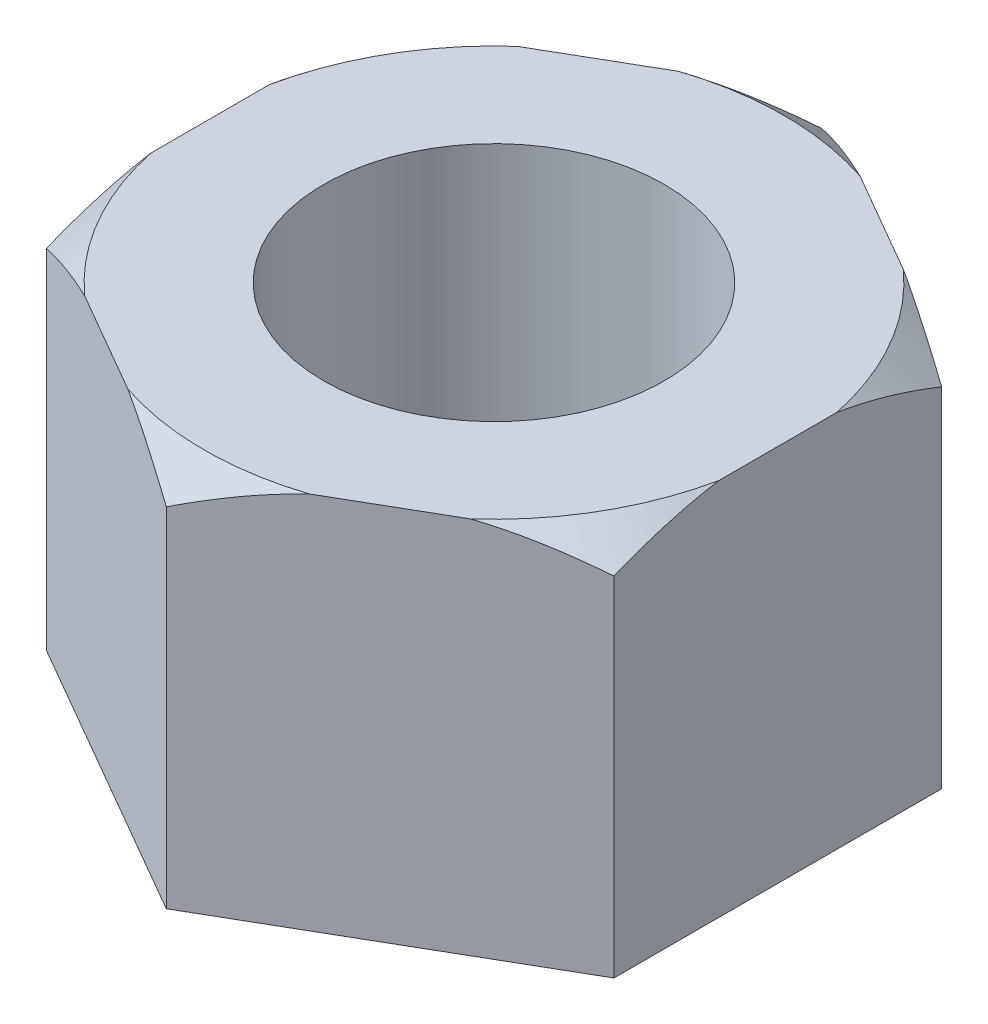
SolidWorks part; units mm, degrees
ref_plane "Front Plane" through (0, 0, 0) normal (0, 0, 1) x (1, 0, 0)
ref_plane "Top Plane" through (0, 0, 0) normal (0, 1, 0) x (1, 0, 0)
ref_plane "Right Plane" through (0, 0, 0) normal (1, 0, 0) x (0, 0, -1)
sketch "Sketch1" plane through (0, 0, 0) normal (0, 1, 0) x (1, 0, 0)
  line L1 (7.5, 4.3301) -> (0, 8.6603)
  line L2 (0, 8.6603) -> (-7.5, 4.3301)
  line L3 (-7.5, 4.3301) -> (-7.5, -4.3301)
  line L4 (-7.5, -4.3301) -> (0, -8.6603)
  line L5 (0, -8.6603) -> (7.5, -4.3301)
  line L6 (7.5, -4.3301) -> (7.5, 4.3301)
  circle A0 centre (0, 0) radius 7.5 construction
  dimension "D1" = 15
extrude "Boss-Extrude1" add sketch "Sketch1" along normal blind 10
sketch "Sketch2" plane through (0, 10, 0) normal (0, 1, 0) x (1, 0, 0)
  circle A0 centre (0, 0) radius 4.5
  dimension "D1" = 4.5
sketch "Sketch3" plane through (0, 0, 0) normal (1, 0, 0) x (0, 0, -1)
  line L0 (0, 0) -> (0, 10.0426) construction
  line L1 (-8.6603, 10) -> (-7.6603, 10)
  line L2 (-7.6603, 10) -> (-8.6603, 9.2)
  line L3 (-8.6603, 9.2) -> (-8.6603, 10)
  line L4 (-8.6603, 10) -> (-4.3301, 10) construction
  line L5 (-8.6603, 10) -> (-8.6603, 0) construction
  dimension "D1" = 1
  dimension "D2" = 0.8
revolve "Cut-Revolve1" cut sketch "Sketch3" angle 360 about L0
extrude "Cut-Extrude1" cut sketch "Sketch2" against normal blind 10
cosmetic thread "Cosmetic Thread1" parameters "D2"=10
